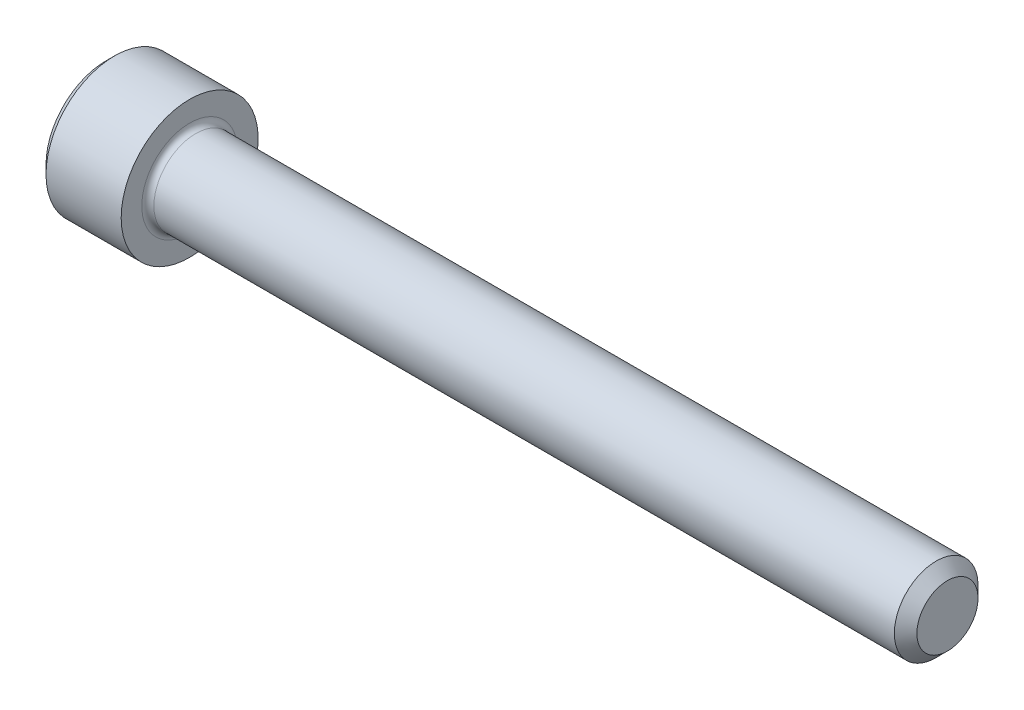
SolidWorks part; units mm, degrees
ref_plane "Plane1" through (0, 0, 0) normal (0, 0, 1) x (1, 0, 0)
ref_plane "Plane2" through (0, 0, 0) normal (0, 1, 0) x (1, 0, 0)
ref_plane "Plane3" through (0, 0, 0) normal (1, 0, 0) x (0, 0, -1)
revolve "Base-Revolve" add sketch "BodySke"
sketch "BodySke" plane through (0, 0, 0) normal (0, 0, 1) x (1, 0, 0)
  line L0 (0, 0) -> (0, 2.5146)
  line L1 (0.3556, 2.8702) -> (3.5052, 2.8702)
  line L2 (3.5052, 2.8702) -> (3.5052, 1.7526)
  line L3 (3.5052, 1.7526) -> (34.7828, 1.7526)
  line L4 (35.2552, 1.2802) -> (35.2552, 0)
  line L5 (35.2552, 0) -> (0, 0)
  line L6 (-31.75, 0) -> (127, 0) construction
  line L7 (0, 2.5146) -> (0.3556, 2.8702)
  line L8 (35.2552, 1.2802) -> (34.7828, 1.7526)
  line L9 (0, -2.5146) -> (0.3556, -2.8702) construction
  line L10 (35.2552, -1.2802) -> (34.7828, -1.7526) construction
  line L11 (4.2977, 9.525) -> (4.2977, 3.175) construction
  line L12 (16.2052, 9.525) -> (16.2052, 3.175) construction
  line L13 (-2.8448, 9.525) -> (-2.8448, 3.175) construction
  dimension "Diameter" = 3.5052
  dimension "Head_ht" = 3.5052
  dimension "Length" = 31.75
  dimension "Body_ch_ang" = 45
  dimension "Head_dia" = 5.7404
  dimension "Head_ch_ang" = 45
  dimension "Head_side_ht" = 3.1496
  dimension "Minor_dia" = 2.5603
  dimension "Advance" = 0.7925
  dimension "Thread_nom" = 19.05
  dimension "Thread_length" = 38.1
cosmetic thread "ThreadCosmetic"
fillet "Fillet1" radius 0.254 1 edges at (3.5052, 0, 1.7526)
sketch "Sketch2" plane through (0, 0, 0) normal (0, 0, 1) x (1, 0, 0)
  line L0 (0, 1.3843) -> (1.6256, 1.3843)
  line L1 (1.6256, 1.3843) -> (2.4248, 0)
  line L2 (-31.75, 0) -> (127, 0) construction
  line L3 (2.4248, 0) -> (0, 0)
  line L4 (0, 0) -> (0, 1.3843)
  line L5 (0, 2.5146) -> (0, -2.5146) construction
  line L6 (0, 0) -> (47.625, 0) construction
  line L7 (3.5052, -2.8702) -> (3.5052, 2.8702) construction
  dimension "D1" = 1.3843
  dimension "D2" = 60
  dimension "Wall_thickness" = 1.8796
revolve "Hex-PreBroach" cut sketch "Sketch2" angle 360 about L6
sketch "Sketch3" plane through (0, 0, 0) normal (-1, 0, 0) x (0, 0.5, 0.866)
  line L0 (0.7992, 1.3843) -> (-0.7992, 1.3843)
  line L1 (-0.7992, 1.3843) -> (-1.5985, 0)
  line L2 (0.7992, 1.3843) -> (1.5985, 0)
  line L3 (0.7992, -1.3843) -> (1.5985, 0)
  line L4 (0.7992, -1.3843) -> (-0.7992, -1.3843)
  line L5 (-0.7992, -1.3843) -> (-1.5985, 0)
  dimension "D1" = 1.3843
  dimension "D2" = 1.3843
  dimension "Hex_size" = 2.7686
extrude "Hex" cut sketch "Sketch3" against normal blind 1.6256
sketch "Sketch4" plane through (0, 0, 0) normal (-1, 0, 0) x (0, 0, 1)
  line L0 (0, 0) -> (1.7399, 0)
  line L1 (0, 0) -> (6.1484, 3.5498) construction
  line L2 (0, 0) -> (0.8699, 1.5068)
  line L3 (1.4457, 0.3947) -> (1.6607, 0.5189)
  line L4 (1.0647, 1.0546) -> (1.2797, 1.1788)
  arc A0 (1.4457, 0.3947) -> (1.0647, 1.0546) centre (0, 0) ccw
  arc A1 (1.7399, 0) -> (1.6607, 0.5189) centre (0, 0) ccw
  arc A2 (0.8699, 1.5068) -> (1.2797, 1.1788) centre (0, 0) cw
  dimension "D1" = 30
  dimension "Spline_n_dim" = 2.9972
  dimension "Spline_m_dim" = 3.4798
  dimension "D2" = 60
  dimension "D3" = 0.381
  dimension "Spline_p_dim" = 0.762
extrude "Spline" [suppressed] cut sketch "Sketch4" against normal blind 1.6256
pattern_circular "CirPattern1" [suppressed] count 6 every 60
sketch "Sketch5" plane through (0, 0, 0) normal (0, 0, 1) x (1, 0, 0)
  line L0 (-31.75, 0) -> (127, 0) construction
  line L2 (0, 2.5146) -> (0, -2.5146) construction
  circle A0 centre (1.27, 0) radius 0.4445
  dimension "Drilled_hole_dia" = 0.889
  dimension "Drilled_hole_loc" = 1.27
extrude "Hole" [suppressed] cut sketch "Sketch5" against normal through all and the other way through all
pattern_circular "Drilled-4" [suppressed] count 2 every 60
pattern_circular "Drilled-6" [suppressed] count 3 every 60
sketch "ThdSchSke" plane through (0, 0, 0) normal (0, 0, 1) x (1, 0, 0)
  line L0 (16.2052, -1.2802) -> (15.8744, -1.7526)
  line L1 (16.2052, -1.2802) -> (16.536, -1.7526)
  line L2 (16.536, -1.7526) -> (16.536, -2.1908)
  line L3 (-3.175, 0) -> (5.1513, 0) construction
  line L5 (16.536, -2.1908) -> (15.8744, -2.1908)
  line L6 (15.8744, -2.1908) -> (15.8744, -1.7526)
  line L7 (0, 2.5146) -> (0, -2.5146) construction
  dimension "Thread_minor" = 2.5603
  dimension "Diameter" = 3.5052
  dimension "Start" = 16.2052
  dimension "SideAngle" = 55
  dimension "VeeAngle" = 70
  dimension "Overcut" = 4.3815
revolve "ThreadSchematic" [suppressed] cut sketch "ThdSchSke" angle 360 about L3
pattern_linear "ThdSchPat" [suppressed]
equation "\"D2@Sketch3\" = \"Hex_size@Sketch3\" / 2"
equation "\"D1@Sketch3\" = \"Hex_size@Sketch3\" / 2"
equation "\"D1@Sketch2\" = \"Hex_size@Sketch3\" / 2"
equation "\"D3@Sketch4\" = \"Spline_p_dim@Sketch4\" / 2"
equation "\"Thread_minor@ThreadCosmetic\"  =  \"Minor_dia@BodySke\""
equation "\"D2@CirPattern1\" = 360 / \"Num_teeth@CirPattern1\""
equation "\"Wall_thickness@Sketch2\" = \"Head_ht@BodySke\" - \"Key_eng@Hex\""
equation "\"Thread_length@ThreadCosmetic\" = ((sgn( (\"Length@BodySke\" - \"Advance@BodySke\" ) - \"Thread_nom@BodySke\" )-1)*( (\"Length@BodySke\" - \"Advance@BodySke\" ) - \"Thread_nom@BodySke\" ))/-2+ \"Thread_nom@BodySke\""
equation "\"Thread_minor@ThdSchSke\" = \"Minor_dia@BodySke\""
equation "\"Diameter@ThdSchSke\" = \"Diameter@BodySke\""
equation "\"Overcut@ThdSchSke\" = \"Diameter@BodySke\" * 1.25"
equation "\"Start@ThdSchSke\" = \"Head_ht@BodySke\" + \"Length@BodySke\" - \"Thread_length@ThreadCosmetic\"  '---Non-countersunk---"
equation "\"Num_threads@ThdSchPat\" = int( \"Thread_length@ThreadCosmetic\" / \"Advance@BodySke\" + 0.999 )  + 1"
equation "\"Advance@ThdSchPat\" = \"Thread_length@ThreadCosmetic\" /  (\"Num_threads@ThdSchPat\" - 1) 'relax it"
equation "\"Num_threads@ThdSchPat\" = \"Num_threads@ThdSchPat\" - sgn( \"Num_threads@ThdSchPat\" - 1) '---chamfered tips only---"
